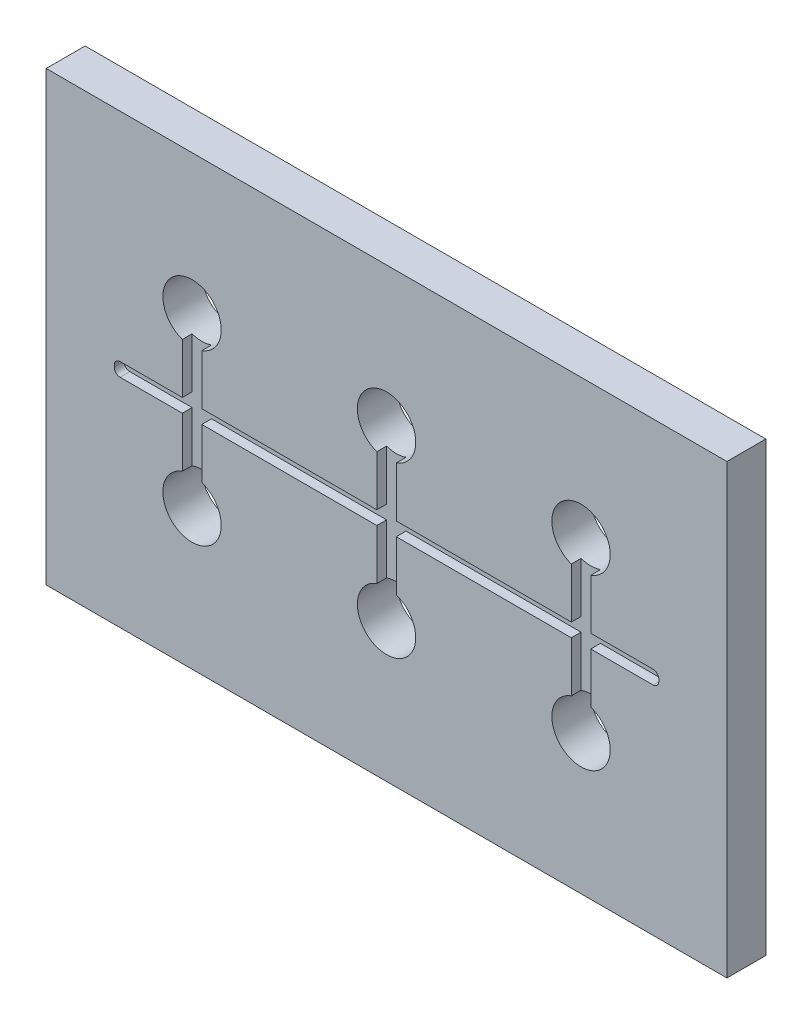
SolidWorks part; units mm, degrees
ref_plane "Front Plane" through (0, 0, 0) normal (0, 0, 1) x (1, 0, 0)
ref_plane "Top Plane" through (0, 0, 0) normal (0, 1, 0) x (1, 0, 0)
ref_plane "Right Plane" through (0, 0, 0) normal (1, 0, 0) x (0, 0, -1)
sketch "Sketch1" plane through (0, 0, 0) normal (0, 0, 1) x (1, 0, 0)
  line L1 (-163.8728, 86.7052) -> (186.1272, 86.7052)
  line L2 (-163.8728, 86.7052) -> (-163.8728, -143.2948)
  line L3 (-163.8728, -143.2948) -> (186.1272, -143.2948)
  line L4 (186.1272, 86.7052) -> (186.1272, -143.2948)
  dimension "D1" = 350
  dimension "D2" = 230
extrude "Boss-Extrude1" add sketch "Sketch1" along normal blind 20
sketch "Sketch3" plane through (0, 0, 20) normal (0, 0, 1) x (1, 0, 0)
  line L0 (-163.8728, 86.7052) -> (-163.8728, -143.2948) construction
  line L1 (-125.8728, -24.7948) -> (-93.8728, -24.7948)
  line L2 (-128.8728, -27.7948) -> (-128.8728, -28.7948)
  line L3 (-125.8728, -31.7948) -> (-93.8728, -31.7948)
  line L4 (151.1272, -27.7948) -> (151.1272, -28.7948)
  line L5 (116.1272, -24.7948) -> (116.1272, 5.2052)
  line L6 (106.1272, -24.7948) -> (106.1272, 5.2052)
  line L7 (106.1272, 5.2052) -> (116.1272, 5.2052)
  line L8 (186.1272, 86.7052) -> (-163.8728, 86.7052) construction
  line L9 (186.1272, -143.2948) -> (186.1272, 86.7052) construction
  line L10 (16.1272, -24.7948) -> (16.1272, 5.2052)
  line L11 (6.1272, 5.2052) -> (16.1272, 5.2052)
  line L12 (6.1272, -24.7948) -> (6.1272, 5.2052)
  line L13 (-83.8728, -24.7948) -> (-83.8728, 5.2052)
  line L14 (-93.8728, 5.2052) -> (-83.8728, 5.2052)
  line L15 (-93.8728, -24.7948) -> (-93.8728, 5.2052)
  line L16 (106.1272, -31.7948) -> (106.1272, -61.7948)
  line L17 (106.1272, -61.7948) -> (116.1272, -61.7948)
  line L18 (116.1272, -61.7948) -> (116.1272, -31.7948)
  line L19 (16.1272, -61.7948) -> (16.1272, -31.7948)
  line L20 (6.1272, -31.7948) -> (6.1272, -61.7948)
  line L21 (6.1272, -61.7948) -> (16.1272, -61.7948)
  line L22 (-83.8728, -61.7948) -> (-83.8728, -31.7948)
  line L23 (-93.8728, -31.7948) -> (-93.8728, -61.7948)
  line L24 (-93.8728, -61.7948) -> (-83.8728, -61.7948)
  line L25 (-83.8728, -24.7948) -> (6.1272, -24.7948)
  line L26 (-83.8728, -31.7948) -> (6.1272, -31.7948)
  line L27 (16.1272, -31.7948) -> (106.1272, -31.7948)
  line L28 (16.1272, -24.7948) -> (106.1272, -24.7948)
  line L29 (116.1272, -31.7948) -> (148.1272, -31.7948)
  line L30 (116.1272, -24.7948) -> (148.1272, -24.7948)
  arc A0 (151.1272, -28.7948) -> (148.1272, -31.7948) centre (148.1272, -28.7948) cw
  arc A1 (151.1272, -27.7948) -> (148.1272, -24.7948) centre (148.1272, -27.7948) ccw
  arc A2 (-128.8728, -28.7948) -> (-125.8728, -31.7948) centre (-125.8728, -28.7948) ccw
  arc A3 (-128.8728, -27.7948) -> (-125.8728, -24.7948) centre (-125.8728, -27.7948) cw
  point P38 (151.1272, -24.7948)
  point P41 (-128.8728, -31.7948)
  point P44 (-128.8728, -24.7948)
  dimension "D12" = 3
  dimension "D1" = 7
  dimension "D2" = 280
  dimension "D3" = 35
  dimension "D4" = 30
  dimension "D5" = 30
  dimension "D6" = 10
  dimension "D7" = 111.5
  dimension "D8" = 70
  dimension "D10" = 30
  dimension "D9" = 3
  dimension "D11" = 3
extrude "Cut-Extrude1" cut sketch "Sketch3" against normal blind 5
sketch "Sketch4" plane through (0, 0, 20) normal (0, 0, 1) x (1, 0, 0)
  line L0 (116.1272, 5.2052) -> (106.1272, 5.2052) construction
  line L1 (106.1272, 5.2052) -> (106.1272, -24.7948) construction
  line L2 (106.1272, -61.7948) -> (116.1272, -61.7948) construction
  line L3 (116.1272, -61.7948) -> (116.1272, -31.7948) construction
  circle A0 centre (111.1272, 15.2052) radius 15
  circle A1 centre (11.1272, 15.2052) radius 15
  circle A2 centre (-88.8728, 15.2052) radius 15
  circle A3 centre (111.1272, -71.7948) radius 15
  circle A4 centre (11.1272, -71.7948) radius 15
  circle A5 centre (-88.8728, -71.7948) radius 15
  dimension "D1" = 30
  dimension "D5" = 30
  dimension "D2" = 10
  dimension "D3" = 5
  dimension "D6" = 10
  dimension "D7" = 5
  dimension "D4" = 3
  dimension "D8" = 3
extrude "Cut-Extrude2" cut sketch "Sketch4" against normal blind 20
